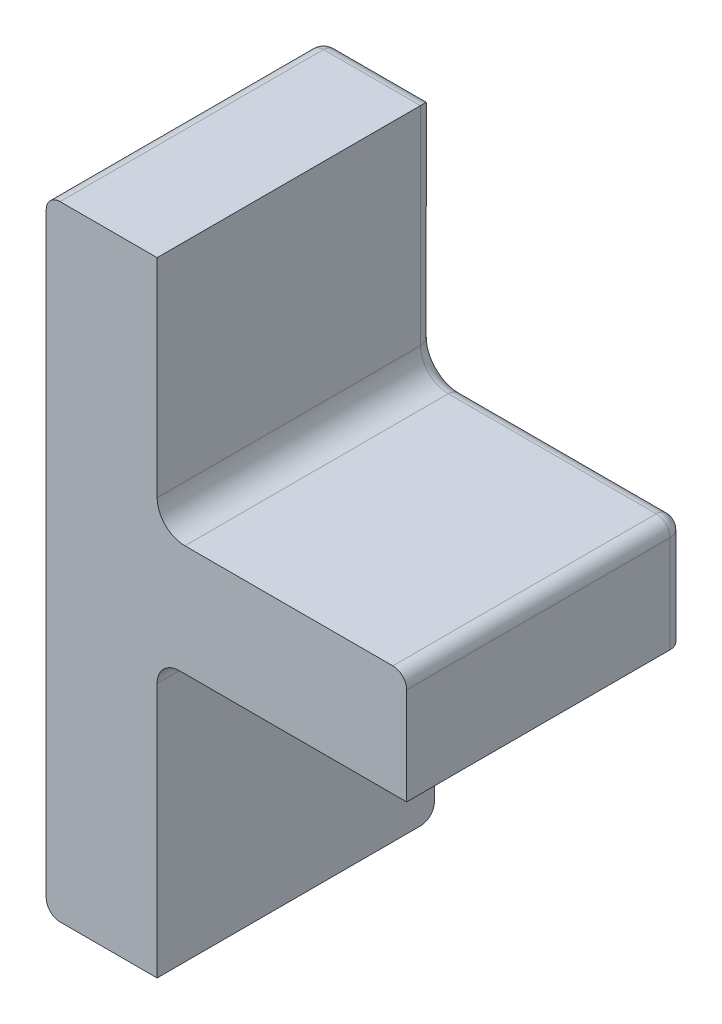
SolidWorks part; units mm, degrees
ref_plane "Front Plane" through (0, 0, 0) normal (0, 0, 1) x (1, 0, 0)
ref_plane "Top Plane" through (0, 0, 0) normal (0, 1, 0) x (1, 0, 0)
ref_plane "Right Plane" through (0, 0, 0) normal (1, 0, 0) x (0, 0, -1)
sketch "Sketch1" plane through (0, 0, 0) normal (0, 0, 1) x (1, 0, 0)
  line L0 (0, 0) -> (0, 35.56)
  line L2 (33.02, 35.56) -> (33.02, 25.4)
  line L3 (33.02, 25.4) -> (12.192, 25.4)
  line L4 (10.16, 23.368) -> (10.16, 0)
  line L5 (10.16, 0) -> (0, 0)
  line L7 (0, 35.56) -> (0, 57.15)
  line L8 (0, 57.15) -> (10.16, 57.15)
  line L9 (10.16, 57.15) -> (10.16, 38.1)
  line L10 (12.7, 35.56) -> (33.02, 35.56)
  arc A3 (12.192, 25.4) -> (10.16, 23.368) centre (12.192, 23.368) ccw
  arc A4 (10.16, 38.1) -> (12.7, 35.56) centre (12.7, 38.1) ccw
  point P20 (10.16, 25.4)
  dimension "D8" = 2.032
  dimension "D11" = 2.54
  dimension "D4" = 33.02
  dimension "D6" = 10.16
  dimension "D10" = 57.15
  dimension "D12" = 23.368
extrude "Boss-Extrude1" add sketch "Sketch1" along normal blind 25.4
fillet "Fillet1" radius 1.27 10 edges at (0, 0, 12.7) (0, 57.15, 12.7) (0, 28.575, 0) (5.08, 0, 0) (10.16, 47.625, 0) (10.9039, 36.3039, 0) (22.86, 35.56, 0) (5.08, 57.15, 0) (33.02, 35.56, 12.7) (33.02, 30.48, 0)
